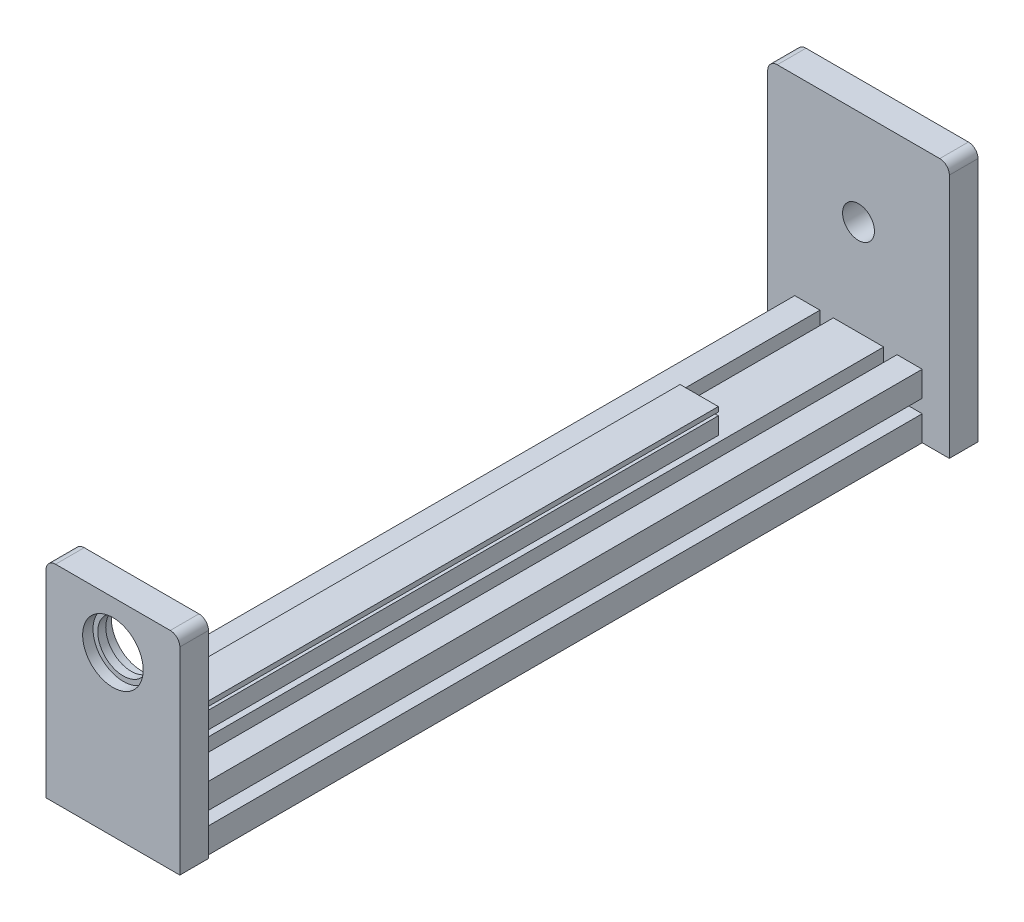
SolidWorks part; units mm, degrees
ref_plane "前视基准面" through (0, 0, 0) normal (0, 0, 1) x (1, 0, 0)
ref_plane "上视基准面" through (0, 0, 0) normal (0, 1, 0) x (1, 0, 0)
ref_plane "右视基准面" through (0, 0, 0) normal (1, 0, 0) x (0, 0, -1)
sketch "草图1" plane through (0, 0, 0) normal (0, 0, 1) x (1, 0, 0)
  line L1 (-25.5, 40) -> (25.5, 40)
  line L2 (-28.5, 37) -> (-28.5, -40)
  line L3 (-28.5, -40) -> (28.5, -40)
  line L4 (28.5, 37) -> (28.5, -40)
  arc A0 (-25.5, 40) -> (-28.5, 37) centre (-25.5, 37) ccw
  arc A1 (28.5, 37) -> (25.5, 40) centre (25.5, 37) ccw
  point P0 (0, 0)
  dimension "D3" = 6
  dimension "D4" = 6
  dimension "D1" = 57
extrude "凸台-拉伸1" add sketch "草图1" along normal blind 9
sketch "草图2" plane through (0, 0, 9) normal (0, 0, 1) x (1, 0, 0)
  line L0 (-28.5, -40) -> (28.5, -40) construction
  line L1 (-20, -40) -> (-12.1, -40)
  line L2 (-20, -40) -> (-20, -32.1)
  line L3 (-20, -20) -> (-12.1, -20)
  line L4 (20, -40) -> (20, -32.1)
  line L5 (28.5, -40) -> (28.5, 37) construction
  line L6 (-12.1, -20) -> (-12.1, -26.2)
  line L7 (-12.1, -26.2) -> (-7.9, -26.2)
  line L8 (-7.9, -26.2) -> (-7.9, -20)
  line L9 (7.9, -20) -> (7.9, -26.2)
  line L10 (7.9, -26.2) -> (12.1, -26.2)
  line L11 (12.1, -26.2) -> (12.1, -20)
  line L12 (-12.1, -40) -> (-12.1, -33.8)
  line L13 (-12.1, -33.8) -> (-7.9, -33.8)
  line L14 (-7.9, -33.8) -> (-7.9, -40)
  line L15 (7.9, -40) -> (7.9, -33.8)
  line L16 (7.9, -33.8) -> (12.1, -33.8)
  line L17 (12.1, -33.8) -> (12.1, -40)
  line L18 (-7.9, -20) -> (7.9, -20)
  line L19 (12.1, -20) -> (20, -20)
  line L20 (-7.9, -40) -> (7.9, -40)
  line L21 (12.1, -40) -> (20, -40)
  line L22 (-20, -27.9) -> (-20, -20)
  line L23 (-20, -27.9) -> (-13.8, -27.9)
  line L25 (-20, -32.1) -> (-13.8, -32.1)
  line L26 (-13.8, -27.9) -> (-13.8, -32.1)
  line L27 (20, -27.9) -> (13.8, -27.9)
  line L29 (20, -32.1) -> (13.8, -32.1)
  line L30 (13.8, -27.9) -> (13.8, -32.1)
  line L31 (20, -27.9) -> (20, -20)
  dimension "D1" = 20
  dimension "D2" = 40
  dimension "D3" = 8.5
  dimension "D4" = 6.2
  dimension "D5" = 6.2
  dimension "D6" = 4.2
  dimension "D7" = 4.2
  dimension "D8" = 7.9
  dimension "D9" = 7.9
  dimension "D10" = 6.2
  dimension "D11" = 4.2
  dimension "D12" = 6.2
  dimension "D13" = 4.2
  dimension "D14" = 6.2
  dimension "D15" = 4.2
  dimension "D16" = 7.9
  dimension "D17" = 4.2
  dimension "D18" = 6.2
  dimension "D19" = 7.9
extrude "凸台-拉伸2" add sketch "草图2" along normal blind 225
sketch "草图3" plane through (0, 0, 234) normal (0, 0, 1) x (1, 0, 0)
  line L0 (-20, -32.1) -> (-20, -40) construction
  line L1 (-21, -40) -> (21, -40)
  line L2 (-21, -40) -> (-21, 22)
  line L3 (-18, 25) -> (18, 25)
  line L4 (21, -40) -> (21, 22)
  arc A0 (-18, 25) -> (-21, 22) centre (-18, 22) ccw
  arc A1 (21, 22) -> (18, 25) centre (18, 22) ccw
  dimension "D4" = 6
  dimension "D5" = 6
  dimension "D2" = 42
  dimension "D3" = 1
extrude "凸台-拉伸3" add sketch "草图3" along normal blind 9
sketch "草图6" plane through (0, 0, 243) normal (0, 0, 1) x (1, 0, 0)
  line L0 (18, 25) -> (-18, 25) construction
  circle A0 centre (0, 10) radius 9.5
  dimension "D1" = 19
  dimension "D2" = 15
extrude "切除-拉伸3" cut sketch "草图6" against normal blind 3.25
sketch "草图7" plane through (0, 0, 234) normal (0, 0, -1) x (-1, 0, 0)
  line L0 (-18, 25) -> (18, 25) construction
  circle A0 centre (0, 10) radius 9.5
  dimension "D1" = 19
  dimension "D2" = 15
extrude "切除-拉伸4" cut sketch "草图7" against normal blind 3.25
sketch "草图8" plane through (0, 0, 234) normal (0, 0, -1) x (-1, 0, 0)
  line L0 (-7.9, -20) -> (7.9, -20) construction
  line L1 (-6, -20) -> (6, -20)
  line L2 (-6, -20) -> (-6, -14.65)
  line L3 (-6, -12.15) -> (6, -12.15)
  line L4 (6, -20) -> (6, -14.65)
  line L5 (6, -13.65) -> (4.5, -13.65)
  line L6 (4.5, -13.65) -> (4.5, -14.65)
  line L7 (4.5, -14.65) -> (6, -14.65)
  line L8 (-6, -13.65) -> (-4.5, -13.65)
  line L9 (-4.5, -13.65) -> (-4.5, -14.65)
  line L10 (-4.5, -14.65) -> (-6, -14.65)
  line L11 (-6, -13.65) -> (-6, -12.15)
  line L12 (6, -13.65) -> (6, -12.15)
  line L13 (7.9, -20) -> (7.9, -26.2) construction
  dimension "D1" = 12
  dimension "D2" = 7.85
  dimension "D3" = 1.5
  dimension "D4" = 1.5
  dimension "D5" = 1
  dimension "D6" = 1
  dimension "D7" = 1.5
  dimension "D8" = 1.9
extrude "凸台-拉伸4" add sketch "草图8" along normal blind 175
sketch "草图10" plane through (0, 0, 239.75) normal (0, 0, 1) x (1, 0, 0)
  circle A0 centre (0, 10) radius 8
  dimension "D1" = 16
extrude "切除-拉伸5" cut sketch "草图10" against normal up to next
sketch "草图11" plane through (0, 0, 0) normal (0, 0, -1) x (-1, 0, 0)
  circle A0 centre (0, 10) radius 5
  dimension "D1" = 10
extrude "切除-拉伸6" cut sketch "草图11" against normal blind 10
